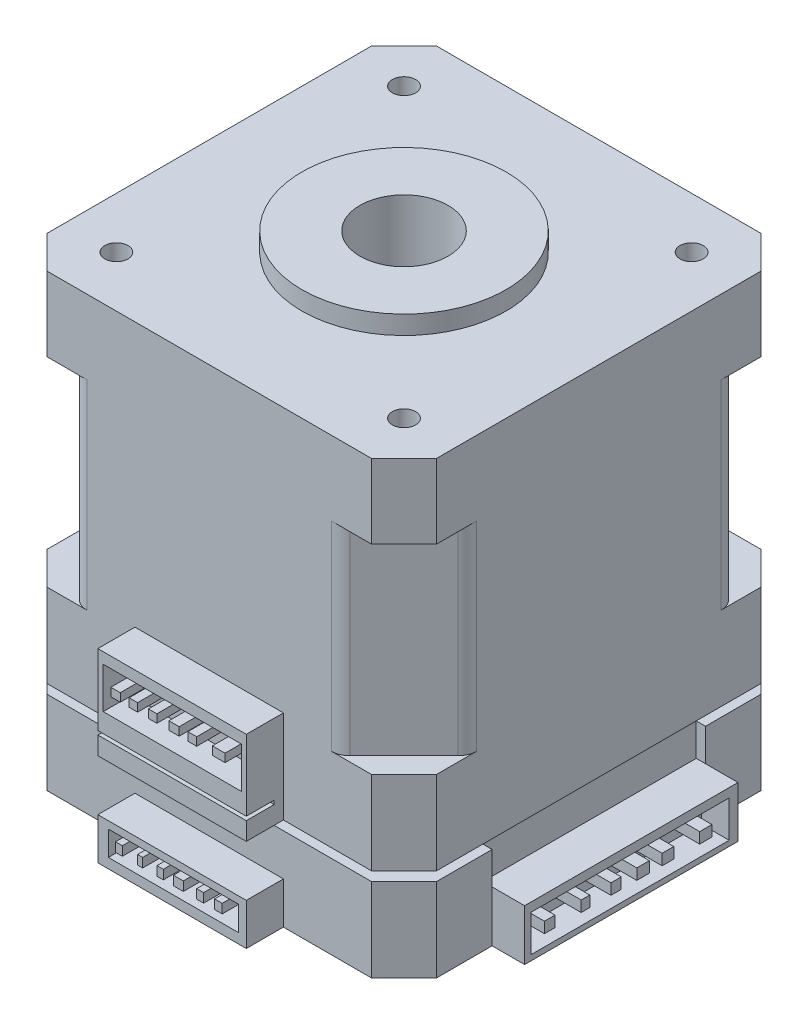
SolidWorks part; units mm, degrees
ref_plane "前视基准面" through (0, 0, 0) normal (0, 0, 1) x (1, 0, 0)
ref_plane "上视基准面" through (0, 0, 0) normal (0, 1, 0) x (1, 0, 0)
ref_plane "右视基准面" through (0, 0, 0) normal (1, 0, 0) x (0, 0, -1)
other "Configuration Table"
sketch "草图1" plane through (0, 0, 0) normal (0, 1, 0) x (1, 0, 0)
  line L0 (-21, 17.5) -> (-17.5, 21)
  line L1 (-17.5, 21) -> (17.5, 21)
  line L2 (-21, 17.5) -> (-21, -17.5)
  line L3 (-17.5, -21) -> (17.5, -21)
  line L4 (21, 17.5) -> (21, -17.5)
  line L5 (-21, 21) -> (21, -21) construction
  line L6 (-21, -21) -> (21, 21) construction
  line L7 (17.5, 21) -> (21, 17.5)
  line L8 (17.5, -21) -> (21, -17.5)
  line L9 (-21, -17.5) -> (-17.5, -21)
  line L11 (-15.5, 15.5) -> (15.5, 15.5) construction
  line L12 (-15.5, 15.5) -> (-15.5, -15.5) construction
  line L13 (-15.5, -15.5) -> (15.5, -15.5) construction
  line L14 (15.5, 15.5) -> (15.5, -15.5) construction
  line L15 (-15.5, 15.5) -> (15.5, -15.5) construction
  line L16 (-15.5, -15.5) -> (15.5, 15.5) construction
  circle A0 centre (-15.5, 15.5) radius 0.5
  circle A1 centre (15.5, 15.5) radius 0.5
  circle A2 centre (-15.5, -15.5) radius 0.5
  circle A3 centre (15.5, -15.5) radius 0.5
  point P0 (0, 0)
  point P14 (0, 0)
  dimension "D9" = 1
  dimension "D10" = 1
  dimension "D11" = 1
  dimension "D12" = 1
  dimension "D1" = 42
  dimension "D2" = 42
  dimension "D3" = 31
  dimension "D4" = 31
extrude "凸台-拉伸1" add sketch "草图1" along normal blind 8
sketch "草图2" plane through (0, 0, 0) normal (0, -1, 0) x (1, 0, 0)
  line L0 (-20.4142, 14.5858) -> (-14.5858, 20.4142)
  line L1 (-13.1716, 21) -> (13.1716, 21)
  line L2 (-21, 13.1716) -> (-21, -13.1716)
  line L3 (-13.1716, -21) -> (13.1716, -21)
  line L4 (21, 13.1716) -> (21, -13.1716)
  line L5 (-21, 21) -> (21, -21) construction
  line L6 (-21, -21) -> (21, 21) construction
  line L7 (14.5858, 20.4142) -> (20.4142, 14.5858)
  line L8 (14.5858, -20.4142) -> (20.4142, -14.5858)
  line L9 (-20.4142, -14.5858) -> (-14.5858, -20.4142)
  arc A0 (-20.4142, 14.5858) -> (-21, 13.1716) centre (-19, 13.1716) ccw
  arc A1 (-20.4142, -14.5858) -> (-21, -13.1716) centre (-19, -13.1716) cw
  arc A2 (-14.5858, -20.4142) -> (-13.1716, -21) centre (-13.1716, -19) ccw
  arc A3 (14.5858, -20.4142) -> (13.1716, -21) centre (13.1716, -19) cw
  arc A4 (20.4142, -14.5858) -> (21, -13.1716) centre (19, -13.1716) ccw
  arc A5 (20.4142, 14.5858) -> (21, 13.1716) centre (19, 13.1716) cw
  arc A6 (14.5858, 20.4142) -> (13.1716, 21) centre (13.1716, 19) ccw
  arc A7 (-14.5858, 20.4142) -> (-13.1716, 21) centre (-13.1716, 19) cw
  point P0 (0, 0)
  point P16 (-21, 14)
  point P19 (-21, -14)
  point P22 (-14, -21)
  point P25 (14, -21)
  point P28 (21, -14)
  point P31 (21, 14)
  point P34 (14, 21)
  point P37 (-14, 21)
  dimension "D2" = 2
extrude "凸台-拉伸2" add sketch "草图2" along normal blind 21.5
sketch "草图3" plane through (0, -21.5, 0) normal (0, -1, 0) x (1, 0, 0)
  line L0 (-21, 17.5) -> (-17.5, 21)
  line L1 (-17.5, 21) -> (17.5, 21)
  line L2 (-21, 17.5) -> (-21, -17.5)
  line L3 (-17.5, -21) -> (17.5, -21)
  line L4 (21, 17.5) -> (21, -17.5)
  line L5 (-21, 21) -> (21, -21) construction
  line L6 (-21, -21) -> (21, 21) construction
  line L7 (17.5, 21) -> (21, 17.5)
  line L8 (17.5, -21) -> (21, -17.5)
  line L9 (-21, -17.5) -> (-17.5, -21)
  point P0 (0, 0)
extrude "凸台-拉伸3" add sketch "草图3" along normal blind 9
sketch "草图4" plane through (0, -30.5, 0) normal (0, -1, 0) x (1, 0, 0)
  line L1 (-15.5, 15.5) -> (15.5, 15.5) construction
  line L2 (-15.5, 15.5) -> (-15.5, -15.5) construction
  line L3 (-15.5, -15.5) -> (15.5, -15.5) construction
  line L4 (15.5, 15.5) -> (15.5, -15.5) construction
  line L5 (-15.5, 15.5) -> (15.5, -15.5) construction
  line L6 (-15.5, -15.5) -> (15.5, 15.5) construction
  circle A0 centre (-15.5, 15.5) radius 3
  circle A1 centre (15.5, 15.5) radius 3
  circle A2 centre (-15.5, -15.5) radius 3
  circle A3 centre (15.5, -15.5) radius 3
  point P0 (0, 0)
  dimension "D3" = 6
  dimension "D4" = 6
  dimension "D5" = 6
  dimension "D6" = 6
  dimension "D1" = 31
  dimension "D2" = 31
extrude "凸台-拉伸4" add sketch "草图4" along normal blind 10
sketch "草图5" plane through (0, -40.5, 0) normal (0, -1, 0) x (1, 0, 0)
  line L0 (-21, 17.5) -> (-17.5, 21)
  line L1 (-17.5, 21) -> (17.5, 21)
  line L2 (17.5, 21) -> (21, 17.5)
  line L3 (21, 17.5) -> (21, -17.5)
  line L4 (21, -17.5) -> (17.5, -21)
  line L5 (17.5, -21) -> (-17.5, -21)
  line L6 (-17.5, -21) -> (-21, -17.5)
  line L7 (-21, -17.5) -> (-21, 17.5)
extrude "凸台-拉伸5" add sketch "草图5" against normal blind 9
hole_wizard "M3 螺纹孔的螺纹孔钻头1" positions "草图8" profile "草图9" hole size "M3" standard "GB"
sketch "草图8" plane through (0, 8, 0) normal (0, 1, 0) x (1, 0, 0)
  point P0 (-15.5, 15.5)
  point P3 (15.5, 15.5)
  point P6 (-15.5, -15.5)
  point P9 (15.5, -15.5)
sketch "草图9" plane through (-15.5, 8, -15.5) normal (1, 0, 0) x (0, 0, 1)
  line L0 (0, 0) -> (0, 7.2511)
  line L1 (0, 7.2511) -> (1.25, 6.5)
  line L2 (1.25, 6.5) -> (1.25, 0)
  line L5 (1.25, 0) -> (0, 0)
  line L10 (0, 7.2511) -> (-1.25, 6.5) construction
  line L11 (0, -6.35) -> (0, 107.95) construction
  dimension "孔直径" = 2.5
  dimension "孔深度" = 6.5
  dimension "导头角度" = 118
cosmetic thread "装饰螺纹线1" parameters "D2"=3
cosmetic thread "装饰螺纹线2" parameters "D2"=3
cosmetic thread "装饰螺纹线3" parameters "D2"=3
cosmetic thread "装饰螺纹线4" parameters "D2"=3
sketch "草图10" plane through (0, 8, 0) normal (0, 1, 0) x (1, 0, 0)
  circle A0 centre (0, 0) radius 11
  dimension "D1" = 22
extrude "凸台-拉伸6" add sketch "草图10" along normal blind 2
sketch "草图11" plane through (0, 10, 0) normal (0, 1, 0) x (1, 0, 0)
  circle A0 centre (0, 0) radius 4.75
  dimension "D1" = 9.5
extrude "切除-拉伸1" cut sketch "草图11" against normal blind 22
sketch "草图12" plane through (0, -40.5, 0) normal (0, -1, 0) x (1, 0, 0)
  line L0 (0, 0) -> (0, 28.793) construction
  line L1 (17.5, 21) -> (-17.5, 21) construction
  line L2 (-8, 21) -> (8, 21)
  line L3 (-8, 21) -> (-8, 25)
  line L4 (-8, 25) -> (8, 25)
  line L5 (8, 21) -> (8, 25)
  dimension "D1" = 4
  dimension "D2" = 16
  dimension "D3" = 8
extrude "凸台-拉伸7" add sketch "草图12" against normal blind 20
sketch "草图13" plane through (0, 0, 25) normal (0, 0, 1) x (1, 0, 0)
  line L0 (-8, -20.5) -> (-8, -40.5) construction
  line L1 (-8, -30.5) -> (8, -30.5)
  line L2 (-8, -30.5) -> (-8, -36)
  line L3 (-8, -36) -> (8, -36)
  line L4 (8, -30.5) -> (8, -36)
  line L5 (8, -31.5) -> (8, -40.5) construction
  dimension "D1" = 5.5
extrude "切除-拉伸2" cut sketch "草图13" against normal blind 4
sketch "草图14" plane through (0, 0, 25) normal (0, 0, 1) x (1, 0, 0)
  line L0 (-8, -20.5) -> (-8, -30.5) construction
  line L1 (-8, -28.1506) -> (8, -28.1506)
  line L2 (-8, -28.1506) -> (-8, -28.5615)
  line L3 (-8, -28.5615) -> (8, -28.5615)
  line L4 (8, -28.1506) -> (8, -28.5615)
  line L5 (8, -20.5) -> (8, -30.5) construction
extrude "切除-拉伸3" cut sketch "草图14" against normal blind 3
sketch "草图15" plane through (0, 0, 25) normal (0, 0, 1) x (1, 0, 0)
  line L1 (-7.4236, -21.6727) -> (7.5085, -21.6727)
  line L2 (-7.4236, -21.6727) -> (-7.4236, -26.0938)
  line L3 (-7.4236, -26.0938) -> (7.5085, -26.0938)
  line L4 (7.5085, -21.6727) -> (7.5085, -26.0938)
  line L5 (-6.6, -23.4065) -> (-5.5814, -23.4065)
  line L6 (-6.6, -23.4065) -> (-6.6, -24.295)
  line L7 (-6.6, -24.295) -> (-5.5814, -24.295)
  line L8 (-5.5814, -23.4065) -> (-5.5814, -24.295)
  line L9 (-4.6279, -23.4065) -> (-3.7176, -23.4065)
  line L10 (-4.6279, -23.4065) -> (-4.6279, -24.295)
  line L11 (-4.6279, -24.295) -> (-3.7176, -24.295)
  line L12 (-3.7176, -23.4065) -> (-3.7176, -24.295)
  line L13 (-2.5473, -23.4065) -> (-1.6371, -23.4065)
  line L14 (-2.5473, -23.4065) -> (-2.5473, -24.295)
  line L15 (-2.5473, -24.295) -> (-1.6371, -24.295)
  line L16 (-1.6371, -23.4065) -> (-1.6371, -24.295)
  line L17 (-0.3368, -23.4065) -> (0.7685, -23.4065)
  line L18 (-0.3368, -23.4065) -> (-0.3368, -24.295)
  line L19 (-0.3368, -24.295) -> (0.7685, -24.295)
  line L20 (0.7685, -23.4065) -> (0.7685, -24.295)
  line L21 (1.7004, -23.4065) -> (2.654, -23.4065)
  line L22 (1.7004, -23.4065) -> (1.7004, -24.295)
  line L23 (1.7004, -24.295) -> (2.654, -24.295)
  line L24 (2.654, -23.4065) -> (2.654, -24.295)
  line L25 (4.3444, -23.4065) -> (5.7098, -23.4065)
  line L26 (4.3444, -23.4065) -> (4.3444, -24.295)
  line L27 (4.3444, -24.295) -> (5.7098, -24.295)
  line L28 (5.7098, -23.4065) -> (5.7098, -24.295)
  line L29 (-6.8684, -36.7781) -> (7.1614, -36.7781)
  line L30 (-6.8684, -36.7781) -> (-6.8684, -39.4299)
  line L31 (-6.8684, -39.4299) -> (7.1614, -39.4299)
  line L32 (7.1614, -36.7781) -> (7.1614, -39.4299)
  line L33 (-6.0907, -37.5798) -> (-5.3575, -37.5798)
  line L34 (-6.0907, -37.5798) -> (-6.0907, -38.5665)
  line L35 (-6.0907, -38.5665) -> (-5.3575, -38.5665)
  line L36 (-5.3575, -37.5798) -> (-5.3575, -38.5665)
  line L37 (-3.7176, -37.5798) -> (-3.1682, -37.5798)
  line L38 (-3.7176, -37.5798) -> (-3.7176, -38.5665)
  line L39 (-3.7176, -38.5665) -> (-3.1682, -38.5665)
  line L40 (-3.1682, -37.5798) -> (-3.1682, -38.5665)
  line L41 (-1.6371, -37.5798) -> (-0.9481, -37.5798)
  line L42 (-1.6371, -37.5798) -> (-1.6371, -38.5665)
  line L43 (-1.6371, -38.5665) -> (-0.9481, -38.5665)
  line L44 (-0.9481, -37.5798) -> (-0.9481, -38.5665)
  line L45 (0.1465, -37.5798) -> (1.2103, -37.5798)
  line L46 (0.1465, -37.5798) -> (0.1465, -38.5665)
  line L47 (0.1465, -38.5665) -> (1.2103, -38.5665)
  line L48 (1.2103, -37.5798) -> (1.2103, -38.5665)
  line L49 (2.654, -37.5798) -> (3.3996, -37.5798)
  line L50 (2.654, -37.5798) -> (2.654, -38.5665)
  line L51 (2.654, -38.5665) -> (3.3996, -38.5665)
  line L52 (3.3996, -37.5798) -> (3.3996, -38.5665)
  line L53 (4.5713, -37.5798) -> (5.4039, -37.5798)
  line L54 (4.5713, -37.5798) -> (4.5713, -38.5665)
  line L55 (4.5713, -38.5665) -> (5.4039, -38.5665)
  line L56 (5.4039, -37.5798) -> (5.4039, -38.5665)
extrude "切除-拉伸4" cut sketch "草图15" against normal blind 3
sketch "草图16" plane through (0, -40.5, 0) normal (0, -1, 0) x (1, 0, 0)
  line L0 (0, 0) -> (31.1349, 0) construction
  line L1 (21, -17.5) -> (21, 17.5) construction
  line L2 (21, 11.5) -> (24.5, 11.5)
  line L3 (21, 11.5) -> (21, -11.5)
  line L4 (21, -11.5) -> (24.5, -11.5)
  line L5 (24.5, 11.5) -> (24.5, -11.5)
  dimension "D1" = 23
  dimension "D2" = 11.5
  dimension "D3" = 11.5
  dimension "D4" = 3.5
extrude "凸台-拉伸8" add sketch "草图16" against normal blind 5.5
sketch "草图17" plane through (21, 0, 0) normal (1, 0, 0) x (0, 0, -1)
  line L0 (17.5, -31.5) -> (-17.5, -31.5) construction
  line L1 (-11.5, -35) -> (11.5, -35)
  line L2 (-11.5, -35) -> (-11.5, -31.5)
  line L3 (-11.5, -31.5) -> (11.5, -31.5)
  line L4 (11.5, -35) -> (11.5, -31.5)
extrude "切除-拉伸5" cut sketch "草图17" against normal blind 1
sketch "草图18" plane through (24.5, 0, 0) normal (1, 0, 0) x (0, 0, -1)
  line L1 (-10.8295, -35.9586) -> (10.5475, -35.9586)
  line L2 (-10.8295, -35.9586) -> (-10.8295, -39.9162)
  line L3 (-10.8295, -39.9162) -> (10.5475, -39.9162)
  line L4 (10.5475, -35.9586) -> (10.5475, -39.9162)
  line L5 (-9.3604, -37.5177) -> (-8.2211, -37.5177)
  line L6 (-9.3604, -37.5177) -> (-9.3604, -38.687)
  line L7 (-9.3604, -38.687) -> (-8.2211, -38.687)
  line L8 (-8.2211, -37.5177) -> (-8.2211, -38.687)
  line L9 (-5.4028, -37.5177) -> (-4.4734, -37.5177)
  line L10 (-5.4028, -37.5177) -> (-5.4028, -38.687)
  line L11 (-5.4028, -38.687) -> (-4.4734, -38.687)
  line L12 (-4.4734, -37.5177) -> (-4.4734, -38.687)
  line L13 (-2.1948, -37.5177) -> (-1.0855, -37.5177)
  line L14 (-2.1948, -37.5177) -> (-2.1948, -38.687)
  line L15 (-2.1948, -38.687) -> (-1.0855, -38.687)
  line L16 (-1.0855, -37.5177) -> (-1.0855, -38.687)
  line L17 (0.5935, -37.5177) -> (1.9427, -37.5177)
  line L18 (0.5935, -37.5177) -> (0.5935, -38.687)
  line L19 (0.5935, -38.687) -> (1.9427, -38.687)
  line L20 (1.9427, -37.5177) -> (1.9427, -38.687)
  line L21 (3.3219, -37.5177) -> (4.5811, -37.5177)
  line L22 (3.3219, -37.5177) -> (3.3219, -38.687)
  line L23 (3.3219, -38.687) -> (4.5811, -38.687)
  line L24 (4.5811, -37.5177) -> (4.5811, -38.687)
  line L25 (7.3694, -37.5177) -> (8.6886, -37.5177)
  line L26 (7.3694, -37.5177) -> (7.3694, -38.687)
  line L27 (7.3694, -38.687) -> (8.6886, -38.687)
  line L28 (8.6886, -37.5177) -> (8.6886, -38.687)
extrude "切除-拉伸6" cut sketch "草图18" against normal blind 3
